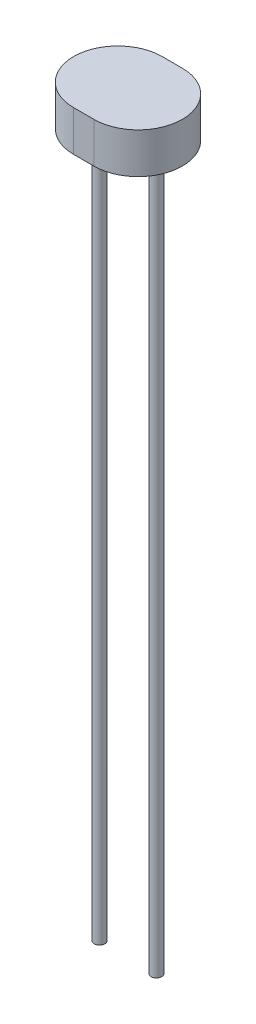
SolidWorks part; units mm, degrees
ref_plane "Alzado" through (0, 0, 0) normal (0, 0, 1) x (1, 0, 0)
ref_plane "Planta" through (0, 0, 0) normal (0, 1, 0) x (1, 0, 0)
ref_plane "Vista lateral" through (0, 0, 0) normal (1, 0, 0) x (0, 0, -1)
sketch "Croquis1" plane through (0, 0, 0) normal (0, 1, 0) x (1, 0, 0)
  line L0 (-0.475, 0) -> (0.475, 0) construction
  line L1 (-0.475, 2.075) -> (0.475, 2.075)
  line L2 (-0.475, -2.075) -> (0.475, -2.075)
  arc A0 (-0.475, 2.075) -> (-0.475, -2.075) centre (-0.475, 0) ccw
  arc A1 (0.475, -2.075) -> (0.475, 2.075) centre (0.475, 0) ccw
  point P3 (0, 0)
  dimension "D1" = 4.15
  dimension "D2" = 0.95
extrude "Saliente-Extruir1" add sketch "Croquis1" along normal blind 1.9
sketch "Croquis3" plane through (0, 0, 0) normal (0, -1, 0) x (1, 0, 0)
  line L0 (0, -1.045) -> (0, 1.045) construction
  circle A0 centre (-1.3337, 0) radius 0.25
  circle A1 centre (1.3337, 0) radius 0.25
  dimension "D1" = 0.5
extrude "Saliente-Extruir2" add sketch "Croquis3" along normal blind 33.4
sketch "Sketch1" plane through (0, 1.9, 0) normal (0, 1, 0) x (1, 0, 0)
  line L0 (-2.55, 0) -> (2.55, 0) construction
  arc A0 (-0.475, 2.075) -> (-0.475, -2.075) centre (-0.475, 0) ccw construction
  arc A1 (0.475, -2.075) -> (0.475, 2.075) centre (0.475, 0) ccw construction
  point P0 (-2.55, 0)
  point P1 (2.55, 0)
  point P5 (0, 0)
